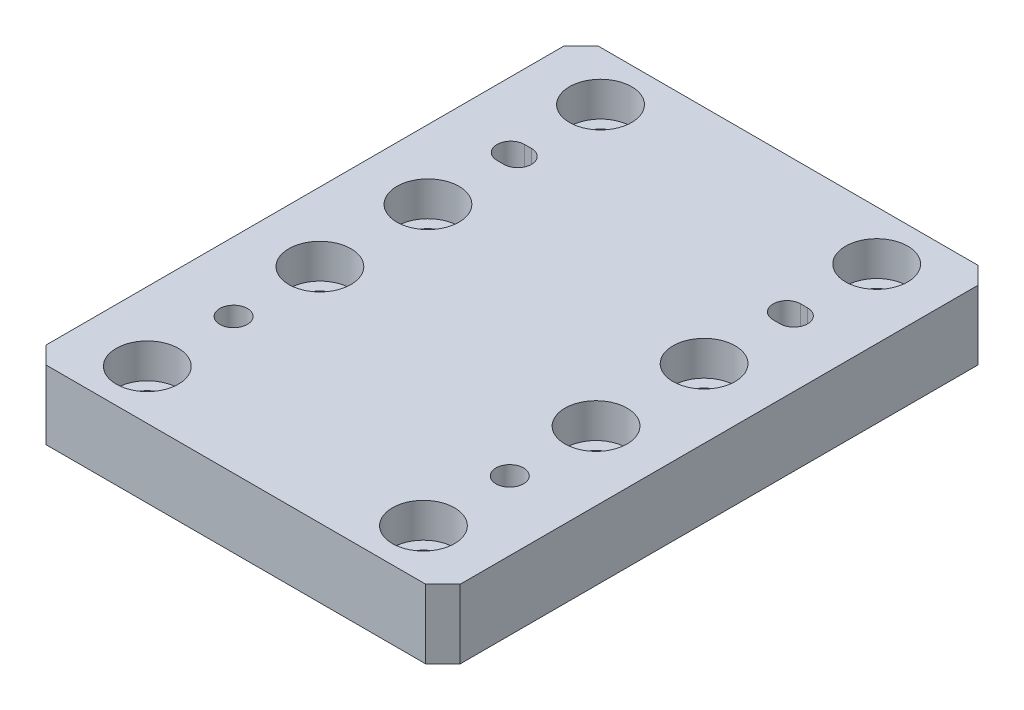
SolidWorks part; units mm, degrees
ref_plane "前基準面" through (0, 0, 0) normal (0, 0, 1) x (1, 0, 0)
ref_plane "上基準面" through (0, 0, 0) normal (0, 1, 0) x (1, 0, 0)
ref_plane "右基準面" through (0, 0, 0) normal (1, 0, 0) x (0, 0, -1)
sketch "草圖1" plane through (0, 0, 0) normal (0, 1, 0) x (1, 0, 0)
  line L0 (-60, -80) -> (60, 80) construction
  line L1 (-60, 80) -> (60, 80)
  line L2 (-60, 80) -> (-60, -80)
  line L3 (-60, -80) -> (60, -80)
  line L4 (60, 80) -> (60, -80)
  dimension "D1" = 120
  dimension "D2" = 160
extrude "伸長1" add sketch "草圖1" along normal blind 20
chamfer "導角1" distance 5 angle 45 4 edges at (-60, 10, 80) (-60, 10, -80) (60, 10, -80) (60, 10, 80)
hole_wizard "M10 六角承窩頭蓋螺釘的柱孔1" positions "草圖3" profile "草圖2" counterbore size "M10" standard "ISO" end condition through all
sketch "草圖3" plane through (0, 20, 0) normal (0, 1, 0) x (-1, 0, 0)
  line L4 (0, -25.3733) -> (0, 0) construction
  line L5 (0, 0) -> (-16.9962, 0) construction
  point P26 (40, -65.65)
  point P28 (40, -15.65)
  point P30 (40, 15.65)
  point P32 (40, 65.65)
  point P34 (-40, -65.65)
  point P36 (-40, -15.65)
  point P38 (-40, 15.65)
  point P40 (-40, 65.65)
  dimension "D1" = 31.3
  dimension "D2" = 50
  dimension "D3" = 80
  dimension "D4" = 50
sketch "草圖2" plane through (-40, 20, -65.65) normal (1, 0, 0) x (0, 0, 1)
  line L0 (0, 0) -> (0, 20)
  line L1 (0, 20) -> (5.5, 20)
  line L3 (5.5, 20) -> (5.5, 10)
  line L4 (5.5, 10) -> (9, 10)
  line L5 (9, 10) -> (9, 0)
  line L7 (9, 0) -> (0, 0)
  line L11 (0, -6.35) -> (0, 107.95) construction
  dimension "貫穿孔直徑" = 11
  dimension "貫穿孔深度" = 20
  dimension "柱孔直徑" = 18
  dimension "柱孔深度" = 10
sketch "草圖6" plane through (0, 20, 0) normal (0, 1, 0) x (1, 0, 0)
  line L0 (-41, 40.65) -> (-39, 40.65) construction
  line L1 (39, 40.65) -> (41, 40.65) construction
  line L4 (40, -15.65) -> (40, -65.65) construction
  line L5 (40, 15.65) -> (40, 65.65) construction
  line L6 (-40, 65.65) -> (-40, 15.65) construction
  line L7 (39, 36.65) -> (41, 36.65)
  line L10 (-41, 36.65) -> (-39, 36.65)
  line L11 (39, 44.65) -> (41, 44.65)
  line L14 (-41, 44.65) -> (-39, 44.65)
  arc A0 (39, 36.65) -> (39, 44.65) centre (39, 40.65) cw
  arc A1 (41, 36.65) -> (41, 44.65) centre (41, 40.65) ccw
  circle A2 centre (40, -40.65) radius 4
  circle A3 centre (-40, -40.65) radius 4
  arc A6 (-41, 36.65) -> (-41, 44.65) centre (-41, 40.65) cw
  arc A7 (-39, 36.65) -> (-39, 44.65) centre (-39, 40.65) ccw
  point P16 (40, 40.65)
  point P21 (-40, 40.65)
  dimension "D4" = 8
  dimension "D1" = 2
  dimension "D2" = 4
  dimension "D3" = 4
extrude "除料-伸長1" cut sketch "草圖6" against normal up to next
